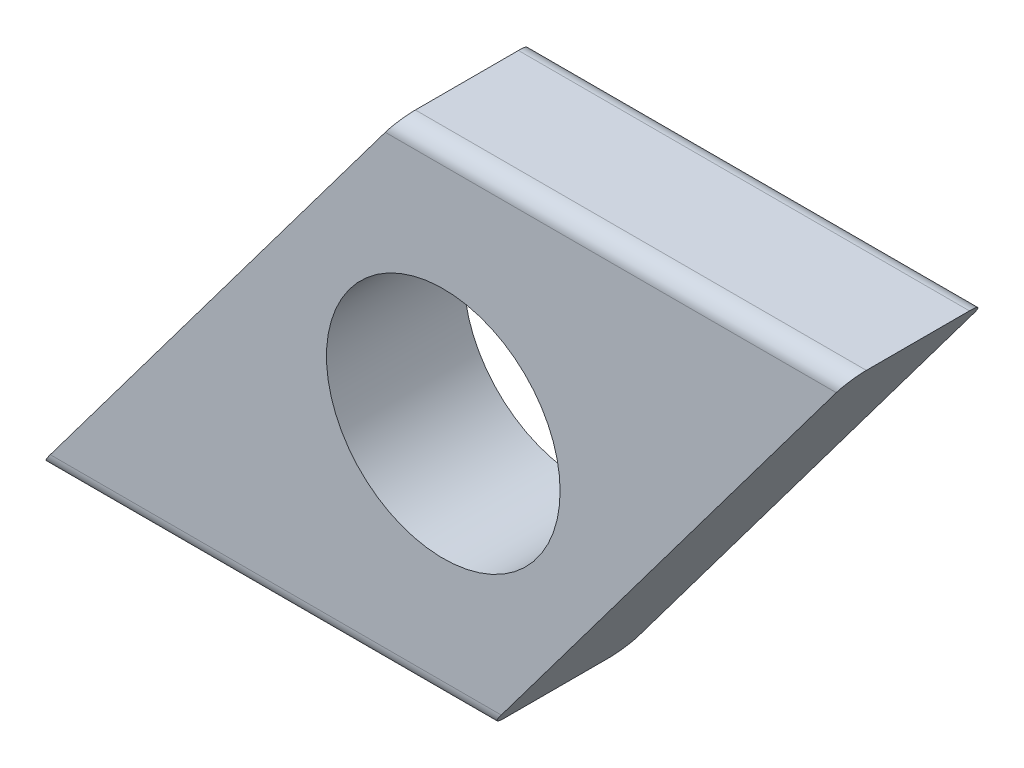
SolidWorks part; units mm, degrees
ref_plane "前视基准面" through (0, 0, 0) normal (0, 0, 1) x (1, 0, 0)
ref_plane "上视基准面" through (0, 0, 0) normal (0, 1, 0) x (1, 0, 0)
ref_plane "右视基准面" through (0, 0, 0) normal (1, 0, 0) x (0, 0, -1)
sketch "草图1" plane through (0, 0, 0) normal (0, 0, 1) x (1, 0, 0)
  line B0 (10.5, 14) -> (0, 0)
  line B1 (0, 0) -> (13.125, 0)
  line B2 (13.125, 0) -> (23.625, 14)
  line B3 (23.625, 14) -> (10.5, 14)
sketch_block_instance "A$C46421FDE-1"
sketch_block "A$C46421FDE"
extrude "凸台-拉伸1" add sketch "草图1" along normal blind 4
sketch "草图3" plane through (0, 0, 4) normal (0, 0, 1) x (1, 0, 0)
  line L0 (0, 0) -> (13.125, 0) construction
  point P0 (11.8125, 7)
  dimension "D1" = 7
hole_wizard "M8 螺纹孔1" positions "3D草图1" profile "草图4" tap size "M8" standard "Iso"
sketch3d "3D草图1"
  point P0 (11.8125, 7, 4)
sketch "草图4" plane through (11.8125, 7, 4) normal (1, 0, 0) x (0, -1, 0)
  line L0 (0, 0) -> (0, 21.7929)
  line L1 (0, 21.7929) -> (3.4, 19.75)
  line L2 (3.4, 19.75) -> (3.4, 0)
  line L5 (3.4, 0) -> (0, 0)
  line L10 (0, 21.7929) -> (-3.4, 19.75) construction
  line L11 (0, -6.35) -> (0, 107.95) construction
  dimension "螺纹孔钻头直径" = 6.8
  dimension "螺纹孔钻头深度" = 19.75
  dimension "导头角度" = 118
cosmetic thread "孔螺蚊线1" parameters "D1"=4, "D2"=8
fillet "圆角1" radius 0.5 4 edges at (17.0625, 14, 0) (17.0625, 14, 4) (6.5625, 0, 0) (6.5625, 0, 4)
